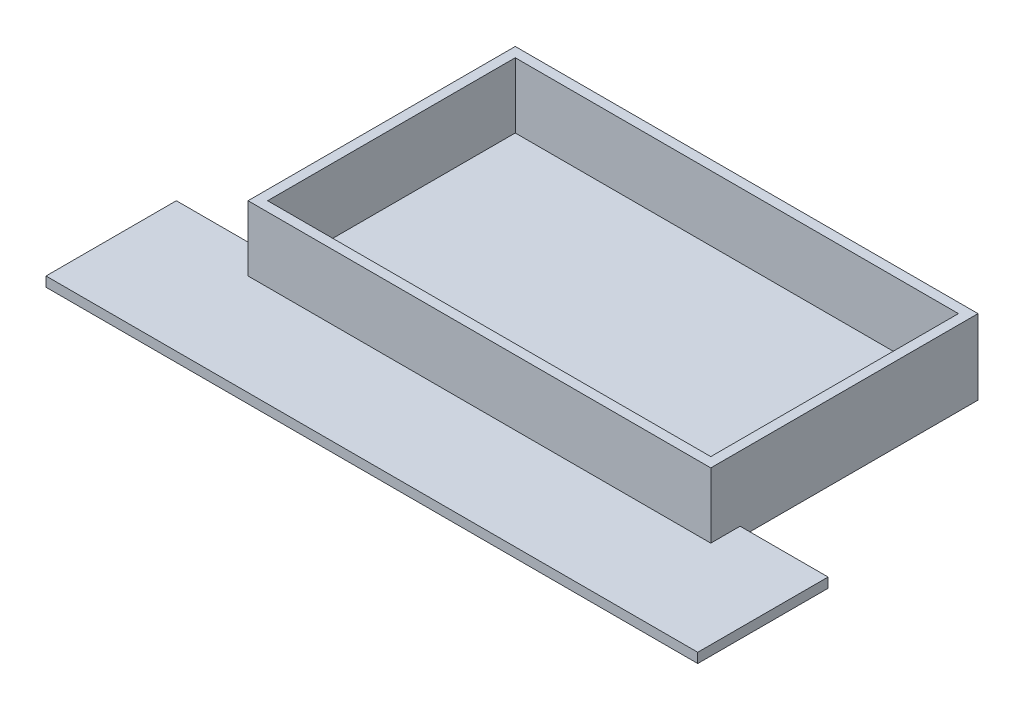
SolidWorks part; units mm, degrees
ref_plane "前视基准面" through (0, 0, 0) normal (0, 0, 1) x (1, 0, 0)
ref_plane "上视基准面" through (0, 0, 0) normal (0, 1, 0) x (1, 0, 0)
ref_plane "右视基准面" through (0, 0, 0) normal (1, 0, 0) x (0, 0, -1)
sketch "草图1" plane through (0, 0, 0) normal (0, 1, 0) x (1, 0, 0)
  line L1 (0, 0) -> (71, 0)
  line L2 (0, 0) -> (0, -41)
  line L3 (0, -41) -> (71, -41)
  line L4 (71, 0) -> (71, -41)
  dimension "D1" = 71
  dimension "D2" = 41
extrude "凸台-拉伸1" add sketch "草图1" along normal blind 1.5
sketch "草图2" plane through (0, 1.5, 0) normal (0, 1, 0) x (1, 0, 0)
  line L0 (1.5, -39.5) -> (1.5, -1.5)
  line L1 (0, -41) -> (71, -41)
  line L2 (0, -41) -> (0, 0)
  line L3 (0, 0) -> (71, 0)
  line L4 (71, -41) -> (71, 0)
  line L5 (1.5, -1.5) -> (69.5, -1.5)
  line L6 (69.5, -39.5) -> (69.5, -1.5)
  line L7 (1.5, -39.5) -> (69.5, -39.5)
  dimension "D1" = 1.5
extrude "凸台-拉伸2" add sketch "草图2" along normal blind 10
sketch "草图3" plane through (0, 0, 0) normal (0, -1, 0) x (-1, 0, 0)
  line L0 (0, 0) -> (0, -41) construction
  line L1 (15.5, -56.5) -> (-84.5, -56.5)
  line L2 (15.5, -56.5) -> (15.5, -36.5)
  line L3 (15.5, -36.5) -> (-84.5, -36.5)
  line L4 (-84.5, -56.5) -> (-84.5, -36.5)
  line L5 (0, -41) -> (-71, -41) construction
  dimension "D1" = 20
  dimension "D2" = 100
  dimension "D3" = 15.5
  dimension "D4" = 15.5
extrude "凸台-拉伸3" add sketch "草图3" against normal blind 1.5
